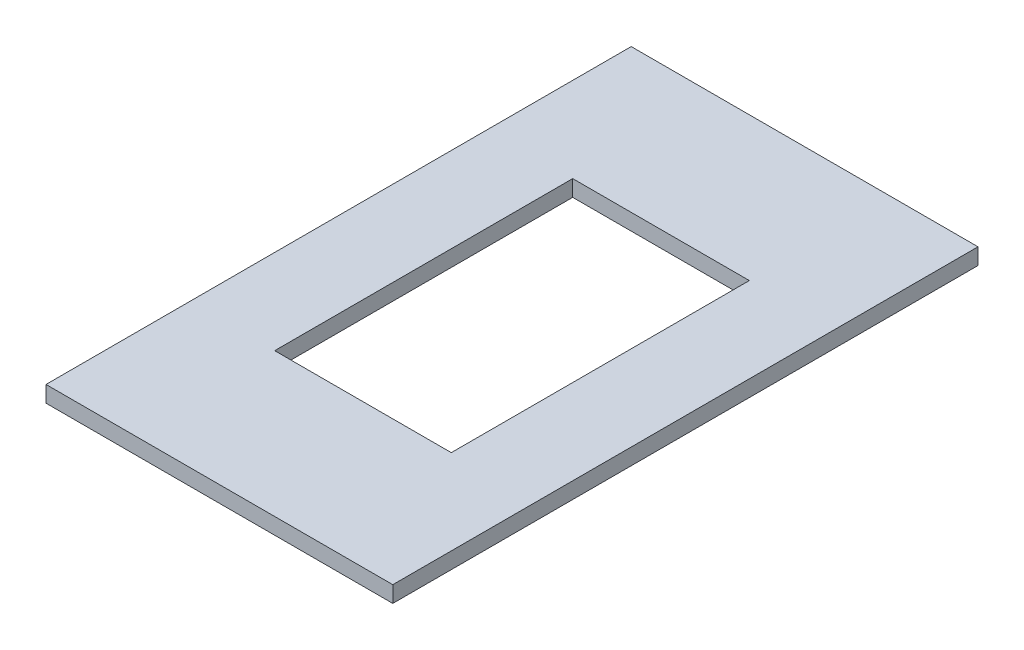
SolidWorks part; units mm, degrees
ref_plane "Front Plane" through (0, 0, 0) normal (0, 0, 1) x (1, 0, 0)
ref_plane "Top Plane" through (0, 0, 0) normal (0, 1, 0) x (1, 0, 0)
ref_plane "Right Plane" through (0, 0, 0) normal (1, 0, 0) x (0, 0, -1)
sketch "Sketch1" plane through (0, 0, 0) normal (0, 1, 0) x (1, 0, 0)
  line L0 (0, 0) -> (0, -360)
  line L1 (0, -360) -> (213.3333, -360)
  line L2 (213.3333, -360) -> (213.3333, 0)
  line L3 (213.3333, 0) -> (0, 0)
  line L4 (213.3333, -360) -> (0, 0) construction
  point P3 (106.6667, -180)
  dimension "D1" = 360
  dimension "D2" = 213.3333
extrude "Boss-Extrude2" add sketch "Sketch1" along normal blind 10
sketch "Sketch2" plane through (0, 10, 0) normal (0, 1, 0) x (1, 0, 0)
  line L0 (0, 0) -> (213.3333, -360) construction
  line L2 (160.9893, -271.6695) -> (52.344, -271.6695)
  line L3 (160.9893, -271.6695) -> (160.9893, -88.3305)
  line L4 (160.9893, -88.3305) -> (52.344, -88.3305)
  line L5 (52.344, -271.6695) -> (52.344, -88.3305)
  line L6 (160.9893, -271.6695) -> (52.344, -88.3305) construction
  line L7 (160.9893, -88.3305) -> (52.344, -271.6695) construction
  point P4 (106.6667, -180)
extrude "Cut-Extrude1" cut sketch "Sketch2" against normal blind 10
ref_plane "Plane13" through (52.344, 0, 88.3305) normal (-1, 0, 0) x (0, 0, 1)
